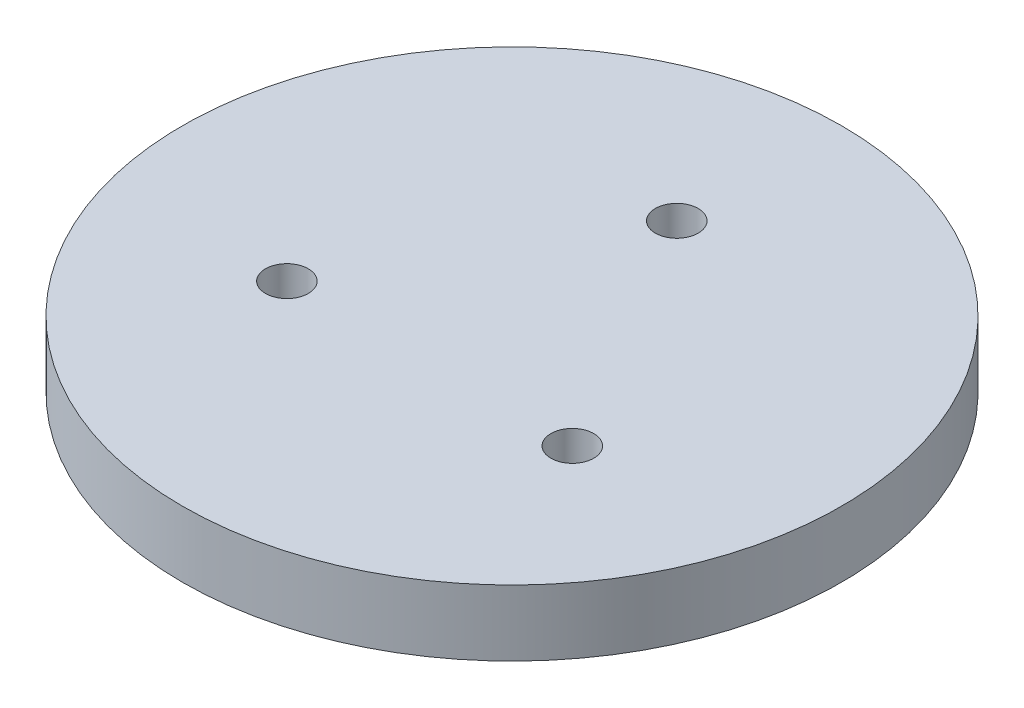
SolidWorks part; units mm, degrees
ref_plane "Front Plane" through (0, 0, 0) normal (0, 0, 1) x (1, 0, 0)
ref_plane "Top Plane" through (0, 0, 0) normal (0, 1, 0) x (1, 0, 0)
ref_plane "Right Plane" through (0, 0, 0) normal (1, 0, 0) x (0, 0, -1)
sketch "Sketch1" plane through (0, 0, 0) normal (0, 1, 0) x (1, 0, 0)
  line L0 (0, 0) -> (0, 50) construction
  circle A0 centre (0, 0) radius 50
  circle A1 centre (0, 25) radius 3.25
  circle A2 centre (21.6506, -12.5) radius 3.25
  circle A3 centre (-21.6506, -12.5) radius 3.25
  point P12 (0, 0)
  dimension "D1" = 100
  dimension "D2" = 6.5
  dimension "D3" = 3
extrude "Boss-Extrude1" add sketch "Sketch1" along normal blind 10
